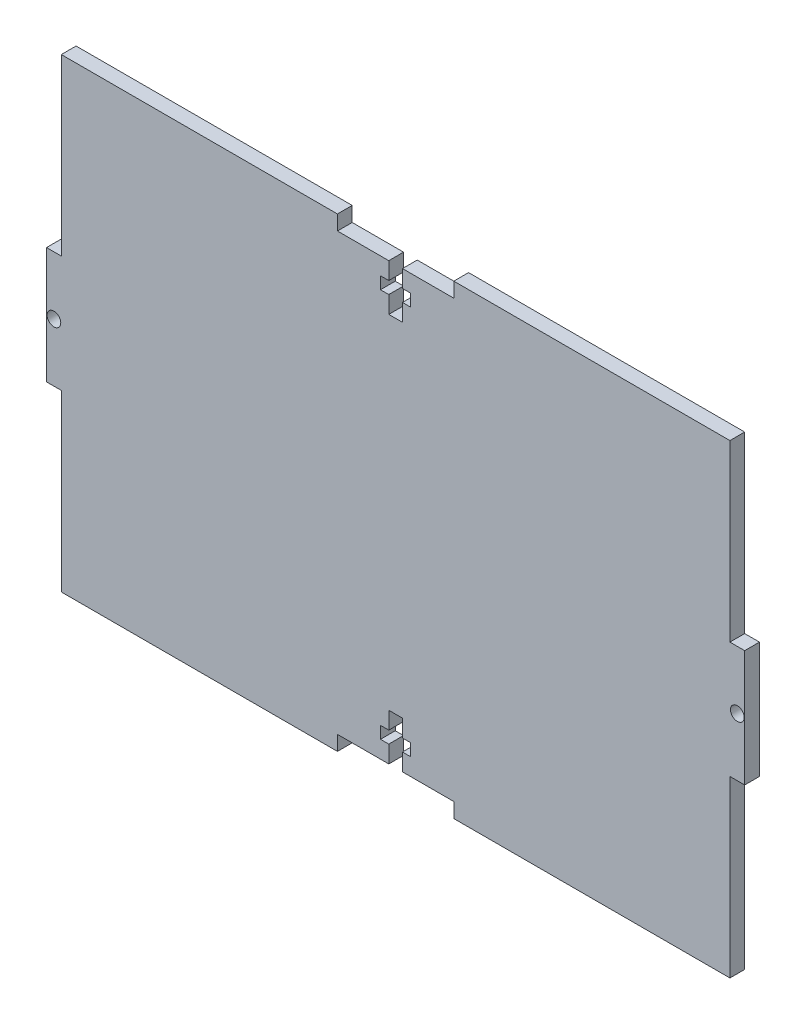
SolidWorks part; units mm, degrees
ref_plane "Front Plane" through (0, 0, 0) normal (0, 0, 1) x (1, 0, 0)
ref_plane "Top Plane" through (0, 0, 0) normal (0, 1, 0) x (1, 0, 0)
ref_plane "Right Plane" through (0, 0, 0) normal (1, 0, 0) x (0, 0, -1)
sketch "Sketch1" plane through (0, 0, 0) normal (0, 0, 1) x (1, 0, 0)
  line L0 (0, 50) -> (0, -50) construction
  line L1 (-71.825, 50) -> (71.825, 50)
  line L2 (-71.825, 50) -> (-71.825, -50)
  line L3 (-71.825, -50) -> (71.825, -50)
  line L4 (71.825, 50) -> (71.825, -50)
  line L5 (-71.825, 50) -> (71.825, -50) construction
  line L6 (-71.825, -50) -> (71.825, 50) construction
  line L7 (-71.825, 0) -> (71.825, 0) construction
  line L8 (-3.25, -40.525) -> (3.25, -40.525)
  line L9 (12.5, 50) -> (-12.5, 50)
  line L10 (12.5, 50) -> (12.5, 46.825)
  line L11 (12.5, 46.825) -> (-12.5, 46.825)
  line L12 (-12.5, 50) -> (-12.5, 46.825)
  line L13 (12.5, 50) -> (-12.5, 46.825) construction
  line L14 (12.5, 46.825) -> (-12.5, 50) construction
  line L15 (-1.47, 46.825) -> (1.47, 46.825)
  line L16 (-1.47, 46.825) -> (-1.47, 36.825)
  line L17 (-1.47, 36.825) -> (1.47, 36.825)
  line L18 (1.47, 46.825) -> (1.47, 36.825)
  line L19 (-1.47, 46.825) -> (1.47, 36.825) construction
  line L20 (-1.47, 36.825) -> (1.47, 46.825) construction
  line L21 (-3.25, 43.125) -> (3.25, 43.125)
  line L22 (-3.25, 43.125) -> (-3.25, 40.525)
  line L23 (-3.25, 40.525) -> (3.25, 40.525)
  line L24 (3.25, 43.125) -> (3.25, 40.525)
  line L25 (-3.25, 43.125) -> (3.25, 40.525) construction
  line L26 (-3.25, 40.525) -> (3.25, 43.125) construction
  line L27 (3.25, -43.125) -> (3.25, -40.525)
  line L28 (-3.25, -43.125) -> (3.25, -43.125)
  line L29 (-3.25, -43.125) -> (-3.25, -40.525)
  line L30 (-1.47, -36.825) -> (1.47, -36.825)
  line L31 (1.47, -46.825) -> (1.47, -36.825)
  line L32 (-1.47, -46.825) -> (1.47, -46.825)
  line L33 (-1.47, -46.825) -> (-1.47, -36.825)
  line L34 (12.5, -46.825) -> (-12.5, -46.825)
  line L35 (-12.5, -50) -> (-12.5, -46.825)
  line L36 (12.5, -50) -> (-12.5, -50)
  line L37 (12.5, -50) -> (12.5, -46.825)
  line L38 (75, -12.5) -> (71.825, -12.5)
  line L39 (-75, 12.5) -> (-71.825, 12.5)
  line L40 (-75, 12.5) -> (-75, -12.5)
  line L41 (-75, -12.5) -> (-71.825, -12.5)
  line L42 (-71.825, 12.5) -> (-71.825, -12.5)
  line L43 (-75, 12.5) -> (-71.825, -12.5) construction
  line L44 (-75, -12.5) -> (-71.825, 12.5) construction
  line L45 (71.825, 12.5) -> (71.825, -12.5)
  line L46 (75, 12.5) -> (71.825, 12.5)
  line L47 (75, 12.5) -> (75, -12.5)
  circle A0 centre (-73.4125, 0) radius 1.47
  circle A1 centre (73.4125, 0) radius 1.47
  point P0 (0, 0)
  point P10 (0, 48.4125)
  point P15 (0, 41.825)
  point P20 (0, 41.825)
  point P37 (-73.4125, 0)
  dimension "D11" = 2.94
  dimension "D1" = 100
  dimension "D2" = 150
  dimension "D3" = 3.175
  dimension "D4" = 10
  dimension "D5" = 2.94
  dimension "D6" = 25
  dimension "D7" = 6.5
  dimension "D8" = 2.6
  dimension "D9" = 6.3
  dimension "D10" = 3.175
extrude "Boss-Extrude1" add sketch "Sketch1" along normal mid plane 3.175 contours L21 L24 L23 L18 L17 L16 L22 L11 L12 L1 L2 L3 L4 L10 | L40 L39 L42 L41 | A0 | L38 L45 L46 L47 | A1
